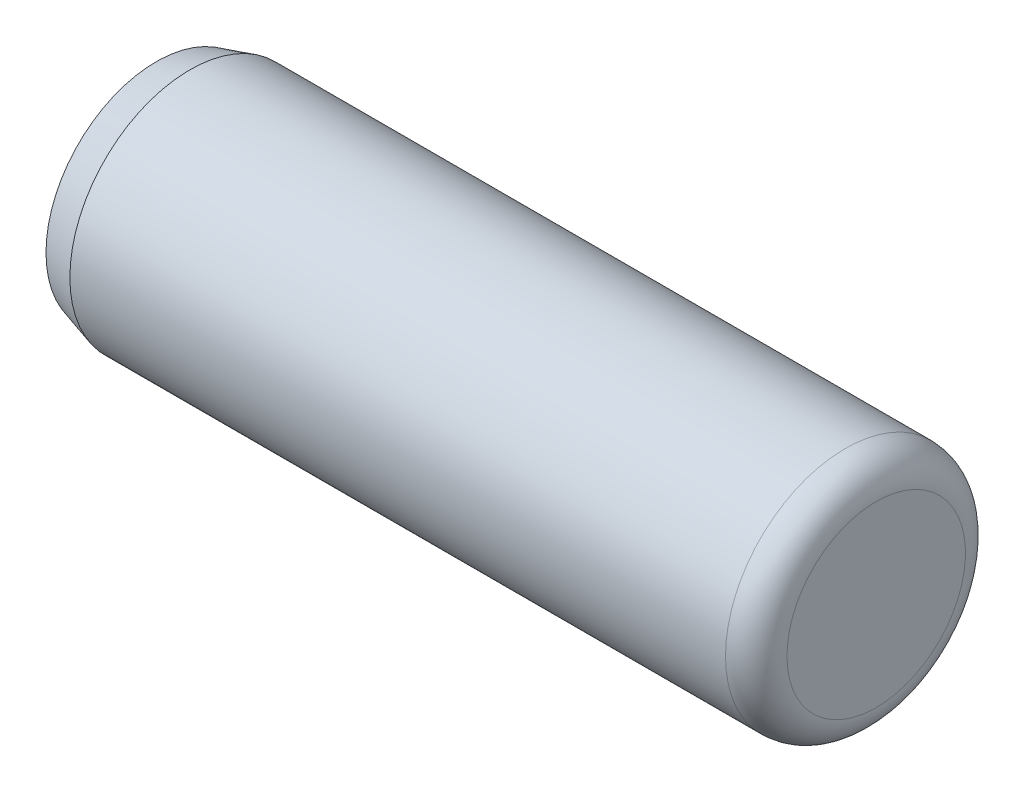
SolidWorks part; units mm, degrees
ref_plane "Front" through (0, 0, 0) normal (0, 0, 1) x (1, 0, 0)
ref_plane "Top" through (0, 0, 0) normal (0, 1, 0) x (1, 0, 0)
ref_plane "Right" through (0, 0, 0) normal (1, 0, 0) x (0, 0, -1)
sketch "Sketch1" plane through (0, 0, 0) normal (1, 0, 0) x (0, 0, -1)
  circle A0 centre (0, 0) radius 1.5875 construction
  point P3 (0, 1.5875)
  dimension "Diameter" = 3.175
sketch "Sketch2" plane through (0, 0, 0) normal (0, 0, 1) x (1, 0, 0)
  line L0 (-4.7625, 0) -> (4.7625, 0) construction
  line L1 (4.7625, 1.1811) -> (4.7625, -0.6481) construction
  line L2 (-4.7625, 1.4605) -> (-4.7625, -1.4605) construction
  line L3 (-4.7625, 1.4605) -> (-4.7625, 1.5875) construction
  line L4 (-4.7625, -1.4605) -> (-4.7625, -1.5875) construction
  line L5 (-4.7625, 1.4605) -> (-4.3196, 1.5875) construction
  line L6 (-4.3196, 1.5875) -> (4.3561, 1.5875) construction
  arc A0 (4.3561, 1.5875) -> (4.7625, 1.1811) centre (4.3561, 1.1811) cw construction
  point P6 (-1.5875, 0)
  point P8 (1.5875, 0)
  point P23 (3.7211, 1.5875)
  dimension "Crown Radius" = 0.4064
  dimension "Length" = 9.525
  dimension "D1" = 3.175
  dimension "D2" = 3.175
  dimension "Point Diameter" = 2.921
  dimension "D3" = 16
  dimension "Crown Height" = 1.0414
sketch "Sketch3" plane through (0, 0, 0) normal (0, 0, 1) x (1, 0, 0)
  line L0 (4.7625, 1.1811) -> (4.7625, -0.6481) construction
  line L1 (-4.3196, 1.5875) -> (4.3561, 1.5875) construction
  line L2 (-4.7625, 1.4605) -> (-4.3196, 1.5875) construction
  line L3 (-4.7625, 1.4605) -> (-4.7625, -1.4605) construction
  line L4 (-4.7625, 0) -> (4.7625, 0) construction
  line L5 (4.7625, 1.1811) -> (4.7625, 0)
  line L6 (-4.3196, 1.5875) -> (4.3561, 1.5875)
  line L7 (-4.7625, 1.4605) -> (-4.3196, 1.5875)
  line L8 (-4.7625, 1.4605) -> (-4.7625, 0)
  line L9 (-4.7625, 0) -> (4.7625, 0)
  arc A0 (4.7625, 1.1811) -> (4.3561, 1.5875) centre (4.3561, 1.1811) ccw construction
  arc A1 (4.7625, 1.1811) -> (4.3561, 1.5875) centre (4.3561, 1.1811) ccw
revolve "Revolve1" add sketch "Sketch3" angle 360 about L0
equation "\"D1@Sketch2\" = \"Diameter@Sketch1\""
equation "\"D2@Sketch2\" = \"Diameter@Sketch1\""
